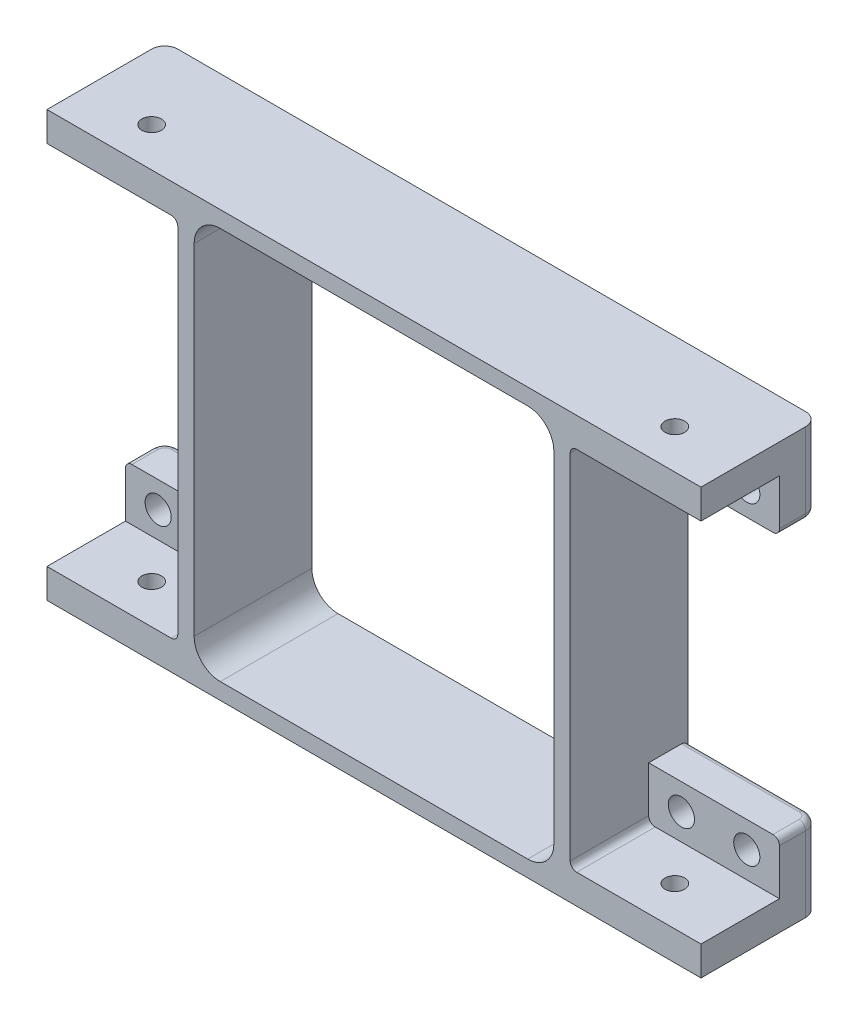
SolidWorks part; units mm, degrees
ref_plane "前视基准面" through (0, 0, 0) normal (0, 0, 1) x (1, 0, 0)
ref_plane "上视基准面" through (0, 0, 0) normal (0, 1, 0) x (1, 0, 0)
ref_plane "右视基准面" through (0, 0, 0) normal (1, 0, 0) x (0, 0, -1)
sketch "草图1" plane through (0, 0, 0) normal (0, 0, 1) x (1, 0, 0)
  line L1 (-50, -32.5) -> (50, -32.5)
  line L2 (-50, -32.5) -> (-50, 32.5)
  line L3 (-50, 32.5) -> (50, 32.5)
  line L4 (50, -32.5) -> (50, 32.5)
  line L5 (-50, -32.5) -> (50, 32.5) construction
  line L6 (-50, 32.5) -> (50, -32.5) construction
  point P0 (0, 0)
  dimension "D1" = 100
  dimension "D2" = 65
extrude "凸台-拉伸1" add sketch "草图1" along normal blind 18
sketch "草图2" plane through (0, 0, 18) normal (0, 0, 1) x (1, 0, 0)
  line L1 (-27.5, -30) -> (27.5, -30)
  line L2 (-27.5, -30) -> (-27.5, 30)
  line L3 (-27.5, 30) -> (27.5, 30)
  line L4 (27.5, -30) -> (27.5, 30)
  line L5 (-27.5, -30) -> (27.5, 30) construction
  line L6 (-27.5, 30) -> (27.5, -30) construction
  point P0 (0, 0)
  dimension "D1" = 55
  dimension "D2" = 60
extrude "切除-拉伸1" cut sketch "草图2" against normal through all
sketch "草图3" plane through (0, 0, 18) normal (0, 0, 1) x (1, 0, 0)
  line L0 (0, 0) -> (50, 0) construction
  line L1 (50, -32.5) -> (50, 32.5) construction
  line L3 (30, -28) -> (50, -28)
  line L4 (30, -28) -> (30, 28)
  line L5 (30, 28) -> (50, 28)
  line L6 (50, -28) -> (50, 28)
  line L7 (30, -28) -> (50, 28) construction
  line L8 (30, 28) -> (50, -28) construction
  point P5 (40, 0)
  dimension "D1" = 56
  dimension "D2" = 20
extrude "切除-拉伸2" cut sketch "草图3" against normal offset from surface (12 mm away) 6 up to face at (0, 0, 0)
sketch "草图4" plane through (0, 0, 6) normal (0, 0, 1) x (1, 0, 0)
  line L0 (50, -28) -> (50, 28) construction
  line L1 (30, -20) -> (50, -20)
  line L2 (30, -20) -> (30, 20)
  line L3 (30, 20) -> (50, 20)
  line L4 (50, -20) -> (50, 20)
  line L5 (30, -20) -> (50, 20) construction
  line L6 (30, 20) -> (50, -20) construction
  line L7 (30, 28) -> (30, -28) construction
  point P0 (40, 0)
  point P9 (0, 0)
  dimension "D1" = 40
extrude "切除-拉伸3" cut sketch "草图4" against normal through all
sketch "草图5" plane through (0, 0, 6) normal (0, 0, 1) x (1, 0, 0)
  line L0 (50, 20) -> (50, 28) construction
  line L1 (50, 20) -> (30, 20) construction
  line L2 (0, 0) -> (54.9836, 0) construction
  circle A0 centre (45, 24) radius 2
  circle A1 centre (35, 24) radius 2
  circle A2 centre (35, -24) radius 2
  circle A3 centre (45, -24) radius 2
  dimension "D1" = 5
  dimension "D2" = 4
  dimension "D3" = 10
  dimension "D4" = 4
extrude "切除-拉伸4" cut sketch "草图5" against normal through all
sketch "草图6" plane through (0, 32.5, 0) normal (0, 1, 0) x (1, 0, 0)
  line L0 (50, -18) -> (50, 0) construction
  line L1 (50, -18) -> (-50, -18) construction
  circle A0 centre (40, -12) radius 1.5
  dimension "D1" = 10
  dimension "D2" = 6
  dimension "D3" = 3
extrude "切除-拉伸5" cut sketch "草图6" against normal through all
mirror "镜向1" about plane through (0, 0, 0) normal (1, 0, 0) of "切除-拉伸5", "切除-拉伸3", "切除-拉伸4", "切除-拉伸2"
fillet "圆角1" radius 4 4 edges at (-27.5, 30, 9) (27.5, 30, 9) (27.5, -30, 9) (-27.5, -30, 9)
fillet "圆角2" radius 2 4 edges at (-50, -26.25, 0) (-50, 26.25, 0) (50, -26.25, 0) (50, 26.25, 0)
fillet "圆角3" radius 1 16 edges at (-39, -20, 0) (-49.4142, -20, 0.5858) (-39, 20, 0) (-49.4142, 20, 0.5858) (39, 20, 0) (49.4142, 20, 0.5858) (39, -20, 0) (49.4142, -20, 0.5858) (-50, -20, 4) (-50, 20, 4) (50, 20, 4) (50, -20, 4) (-30, -28, 12) (-30, 28, 12) (30, 28, 12) (30, -28, 12)
